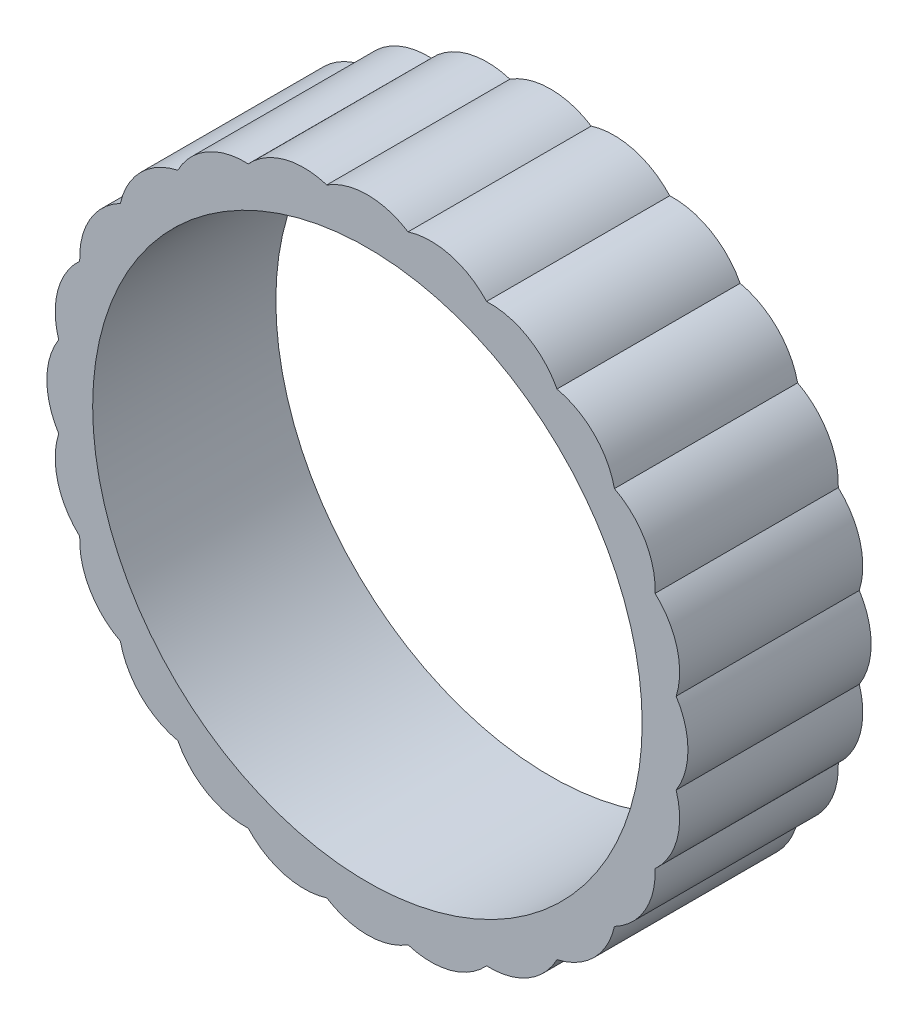
SolidWorks part; units mm, degrees
ref_plane "Front Plane" through (0, 0, 0) normal (0, 0, 1) x (1, 0, 0)
ref_plane "Top Plane" through (0, 0, 0) normal (0, 1, 0) x (1, 0, 0)
ref_plane "Right Plane" through (0, 0, 0) normal (1, 0, 0) x (0, 0, -1)
sketch "Sketch1" plane through (0, 0, 0) normal (0, 0, 1) x (1, 0, 0)
  circle A0 centre (0, 0) radius 17
  circle A1 centre (0, 0) radius 15
  dimension "D1" = 30
  dimension "D2" = 2
extrude "Boss-Extrude1" add sketch "Sketch1" along normal blind 10
sketch "Sketch2" plane through (0, 0, 10) normal (0, 0, 1) x (1, 0, 0)
  line L0 (0, 17) -> (1.1603, 17) construction
  line L2 (0, 17.5) -> (1.2638, 17.5) construction
  arc A0 (-2.2189, 16.8546) -> (2.2189, 16.8546) centre (0, 13.363) cw
  circle A1 centre (0, 0) radius 17 construction
  arc A2 (2.2189, 16.8546) -> (-2.2189, 16.8546) centre (0, 0) ccw
  dimension "D1" = 15
  dimension "D2" = 0.5
extrude "Boss-Extrude2" add sketch "Sketch2" against normal blind 10
pattern_circular "CirPattern1" count 24 over 360 about axis through (0, 0, 0) along (0, 0, 1) of "Boss-Extrude2"
